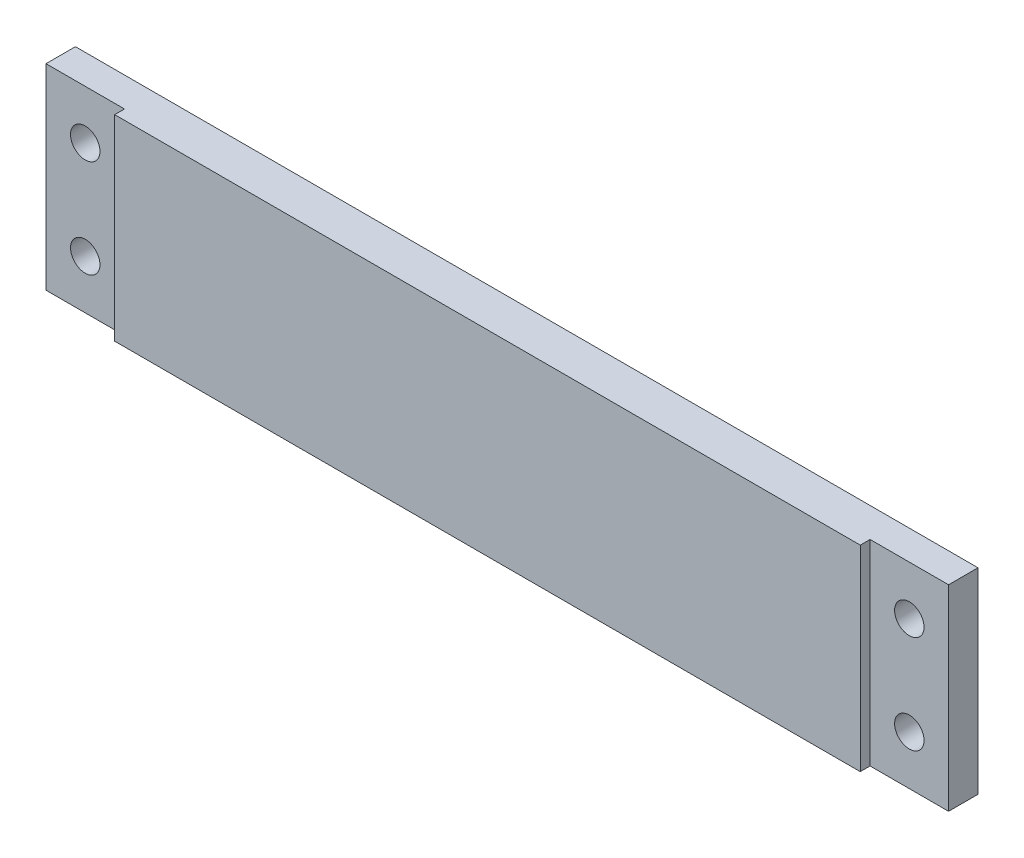
SolidWorks part; units mm, degrees
material "ABS PC"
ref_plane "Front Plane" through (0, 0, 0) normal (0, 0, 1) x (1, 0, 0)
ref_plane "Top Plane" through (0, 0, 0) normal (0, 1, 0) x (1, 0, 0)
ref_plane "Right Plane" through (0, 0, 0) normal (1, 0, 0) x (0, 0, -1)
sketch "Sketch1" plane through (0, 0, 0) normal (0, 0, 1) x (1, 0, 0)
  line L1 (0, 0) -> (92, 0)
  line L2 (0, 0) -> (0, 20)
  line L3 (0, 20) -> (92, 20)
  line L4 (92, 0) -> (92, 20)
  circle A0 centre (4, 15) radius 1.5
  circle A1 centre (4, 5) radius 1.5
  circle A2 centre (88, 5) radius 1.5
  circle A3 centre (88, 15) radius 1.5
  dimension "D5" = 5
  dimension "D3" = 3
  dimension "D1" = 92
  dimension "D2" = 20
  dimension "D4" = 4
  dimension "D6" = 5
  dimension "D7" = 4
extrude "Boss-Extrude1" add sketch "Sketch1" along normal blind 4
sketch "Sketch2" plane through (0, 0, 4) normal (0, 0, 1) x (1, 0, 0)
  line L0 (0, 0) -> (92, 0) construction
  line L1 (0, 20) -> (8, 20)
  line L2 (0, 20) -> (0, 0)
  line L3 (0, 0) -> (8, 0)
  line L4 (8, 20) -> (8, 0)
  line L6 (92, 20) -> (84, 20)
  line L7 (92, 20) -> (92, 0)
  line L8 (92, 0) -> (84, 0)
  line L9 (84, 20) -> (84, 0)
  dimension "D1" = 8
  dimension "D2" = 8
extrude "Cut-Extrude1" cut sketch "Sketch2" against normal blind 1
